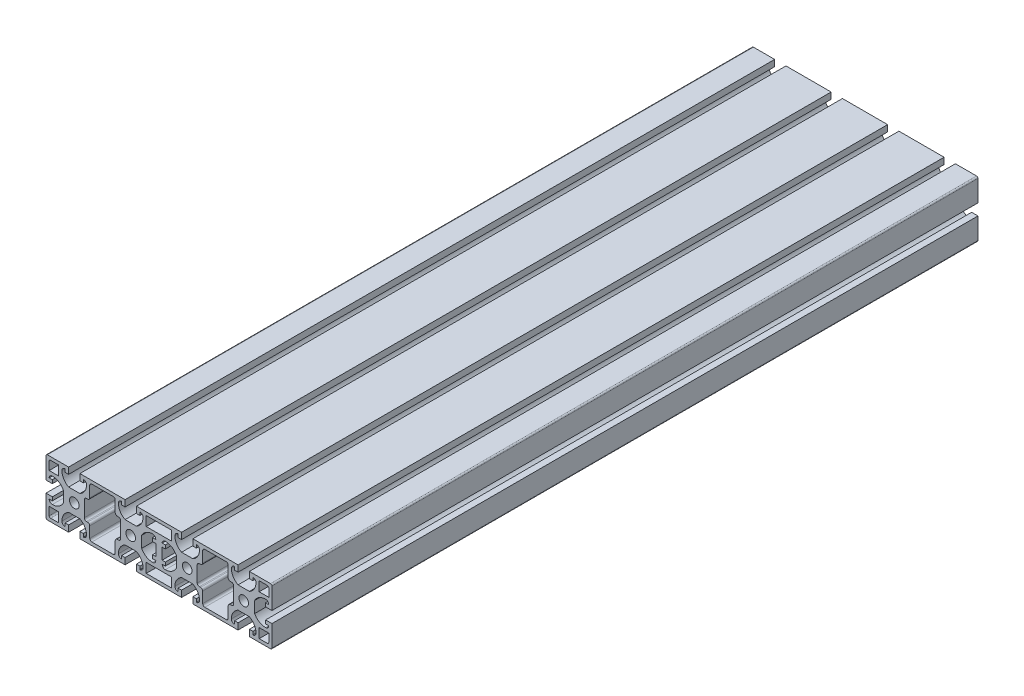
SolidWorks part; units mm, degrees
material "3.0255 (EN-AW 1350A)"
ref_plane "Płaszczyzna przednia" through (0, 0, 0) normal (0, 0, 1) x (1, 0, 0)
ref_plane "Płaszczyzna górna" through (0, 0, 0) normal (0, 1, 0) x (1, 0, 0)
ref_plane "Płaszczyzna prawa" through (0, 0, 0) normal (1, 0, 0) x (0, 0, -1)
sketch "Szkic1" plane through (0, 0, 0) normal (0, 0, 1) x (1, 0, 0)
  line L0 (0, 20) -> (0, -20) construction
  line L1 (-51.8865, 0) -> (40, 0) construction
  line L4 (-40, -20) -> (-40, 20)
  line L7 (-40, -20) -> (0, 0) construction
  line L8 (-40, 20) -> (40, -20) construction
  line L13 (20, 20) -> (20, 0) construction
  line L15 (24, 20) -> (24, 15.5)
  line L16 (24, 15.5) -> (26.4714, 15.5)
  line L21 (16, 15.5) -> (13.5286, 15.5)
  line L23 (16, 20) -> (13.5286, 20)
  line L24 (16, 20) -> (16, 15.5)
  line L25 (16, 7.75) -> (24, 7.75)
  line L26 (13.5286, 15.5) -> (13.5286, 17.75)
  line L27 (26.4714, 15.5) -> (26.4714, 17.75)
  line L28 (-24, 20) -> (-24, 15.5)
  line L29 (-26.4714, 15.5) -> (-26.4714, 17.75)
  line L30 (-24, 15.5) -> (-26.4714, 15.5)
  line L31 (-13.5286, 15.5) -> (-13.5286, 17.75)
  line L32 (-16, 15.5) -> (-13.5286, 15.5)
  line L33 (-16, 20) -> (-16, 15.5)
  line L34 (-16, 7.75) -> (-24, 7.75)
  line L35 (20, -20) -> (20, 0) construction
  line L36 (-40, -20) -> (0, 0) construction
  line L37 (-40, 20) -> (40, -20) construction
  line L38 (30.9714, -17.75) -> (36.75, -17.75)
  line L39 (-16, -7.75) -> (-24, -7.75)
  line L40 (-16, -20) -> (-16, -15.5)
  line L41 (-16, -15.5) -> (-13.5286, -15.5)
  line L42 (-13.5286, -15.5) -> (-13.5286, -17.75)
  line L43 (-24, -15.5) -> (-26.4714, -15.5)
  line L44 (-26.4714, -15.5) -> (-26.4714, -17.75)
  line L45 (-24, -20) -> (-24, -15.5)
  line L46 (26.4714, -15.5) -> (26.4714, -17.75)
  line L47 (13.5286, -15.5) -> (13.5286, -17.75)
  line L48 (16, -7.75) -> (24, -7.75)
  line L49 (16, -20) -> (16, -15.5)
  line L50 (16, -15.5) -> (13.5286, -15.5)
  line L51 (24, -15.5) -> (26.4714, -15.5)
  line L52 (24, -20) -> (24, -15.5)
  line L53 (40, -20) -> (0, 20) construction
  line L54 (35.5, 6.4714) -> (37.75, 6.4714)
  line L55 (35.5, 4) -> (35.5, 6.4714)
  line L56 (40, 4) -> (35.5, 4)
  line L57 (40, -4) -> (35.5, -4)
  line L58 (35.5, -4) -> (35.5, -6.4714)
  line L59 (35.5, -6.4714) -> (37.75, -6.4714)
  line L60 (27.75, 4) -> (27.75, -4)
  line L61 (-35.5, -6.4714) -> (-37.75, -6.4714)
  line L62 (-37.75, -4) -> (-35.5, -4)
  line L63 (-35.5, -4) -> (-35.5, -6.4714)
  line L64 (-35.5, 4) -> (-35.5, 6.4714)
  line L65 (-35.5, 6.4714) -> (-37.75, 6.4714)
  line L66 (-37.75, 4) -> (-35.5, 4)
  line L67 (-27.75, 4) -> (-27.75, -4)
  line L68 (-37.75, 4) -> (-37.75, -4)
  line L69 (40, -4) -> (40, -19)
  line L70 (40, 19) -> (40, 4)
  line L71 (-40, -20) -> (-24, -20)
  line L72 (-16, -20) -> (16, -20)
  line L73 (24, -20) -> (39, -20)
  line L74 (13.5286, 20) -> (-16, 20)
  line L75 (-24, 20) -> (-40, 20)
  line L76 (24, 20) -> (39, 20)
  line L77 (10.5286, 7.0902) -> (11.4095, 7.0902)
  line L78 (-7.5286, -17.75) -> (7.5286, -17.75)
  line L79 (-9.0286, -16.25) -> (-9.0286, -8.5902)
  line L80 (-7.5286, 17.75) -> (7.5286, 17.75)
  line L81 (9.0286, -16.25) -> (9.0286, -8.5902)
  line L82 (-9.0286, -17.75) -> (9.0286, 17.75) construction
  line L83 (-9.0286, 17.75) -> (9.0286, -17.75) construction
  line L84 (-11.4095, -7.0902) -> (-10.5286, -7.0902)
  line L85 (-12.9095, -5.5902) -> (-12.9095, 5.5902)
  line L86 (-11.4095, 7.0902) -> (-10.5286, 7.0902)
  line L87 (12.9095, -5.5902) -> (12.9095, 5.5902)
  line L88 (-12.9095, -7.0902) -> (0, 0) construction
  line L89 (-12.9095, 7.0902) -> (12.9095, -7.0902) construction
  line L90 (-9.0286, 8.5902) -> (-9.0286, 16.25)
  line L91 (-9.0286, 4.5143) -> (-9.0286, 4.9587)
  line L92 (-9.0286, -4.9587) -> (-9.0286, -4.5143)
  line L93 (9.0286, 8.5902) -> (9.0286, 16.25)
  line L94 (10.5286, -7.0902) -> (11.4095, -7.0902)
  line L96 (0, 0) -> (12.9095, 7.0902) construction
  line L98 (37.75, -10.9714) -> (37.75, -16.75)
  line L99 (30.9714, 10.9714) -> (37.75, 10.9714)
  line L100 (30.9714, 10.9714) -> (30.9714, 17.75)
  line L101 (30.9714, 17.75) -> (36.75, 17.75)
  line L102 (37.75, 10.9714) -> (37.75, 16.75)
  line L103 (30.9714, 10.9714) -> (37.75, 17.75) construction
  line L104 (30.9714, 17.75) -> (37.75, 10.9714) construction
  line L105 (30.9714, -10.9714) -> (37.75, -10.9714)
  line L106 (30.9714, -10.9714) -> (30.9714, -17.75)
  line L107 (-30.9714, -10.9714) -> (-30.9714, -17.75)
  line L108 (-30.9714, -10.9714) -> (-37.75, -10.9714)
  line L109 (-37.75, -10.9714) -> (-37.75, -16.75)
  line L110 (-30.9714, -17.75) -> (-36.75, -17.75)
  line L111 (-30.9714, 17.75) -> (-36.75, 17.75)
  line L112 (-37.75, 10.9714) -> (-37.75, 16.75)
  line L113 (-30.9714, 10.9714) -> (-37.75, 10.9714)
  line L114 (-30.9714, 10.9714) -> (-30.9714, 17.75)
  line L115 (-40, 52.1634) -> (-40, -64.8993) construction
  line L116 (-110.9714, 17.75) -> (-117.75, 10.9714) construction
  line L117 (-110.9714, 10.9714) -> (-117.75, 17.75) construction
  line L118 (-80, 0) -> (-92.9095, 7.0902) construction
  line L119 (-67.0905, 7.0902) -> (-92.9095, -7.0902) construction
  line L120 (-67.0905, -7.0902) -> (-80, 0) construction
  line L121 (-70.9714, 17.75) -> (-89.0286, -17.75) construction
  line L122 (-70.9714, -17.75) -> (-89.0286, 17.75) construction
  line L123 (-120, -20) -> (-80, 20) construction
  line L124 (-40, 20) -> (-120, -20) construction
  line L125 (-40, -20) -> (-80, 0) construction
  line L126 (-100, -20) -> (-100, 0) construction
  line L127 (-100, 20) -> (-100, 0) construction
  line L128 (-40, 20) -> (-120, -20) construction
  line L129 (-40, -20) -> (-80, 0) construction
  line L130 (-28.1135, 0) -> (-120, 0) construction
  line L131 (-80, 20) -> (-80, -20) construction
  line L132 (-49.0286, 10.9714) -> (-49.0286, 17.75)
  line L133 (-49.0286, 10.9714) -> (-42.25, 10.9714)
  line L134 (-42.25, 10.9714) -> (-42.25, 16.75)
  line L135 (-49.0286, 17.75) -> (-43.25, 17.75)
  line L136 (-49.0286, -17.75) -> (-43.25, -17.75)
  line L137 (-42.25, -10.9714) -> (-42.25, -16.75)
  line L138 (-49.0286, -10.9714) -> (-42.25, -10.9714)
  line L139 (-49.0286, -10.9714) -> (-49.0286, -17.75)
  line L140 (-110.9714, -10.9714) -> (-110.9714, -17.75)
  line L141 (-110.9714, -10.9714) -> (-117.75, -10.9714)
  line L142 (-117.75, 10.9714) -> (-117.75, 16.75)
  line L143 (-110.9714, 17.75) -> (-116.75, 17.75)
  line L144 (-110.9714, 10.9714) -> (-110.9714, 17.75)
  line L145 (-110.9714, 10.9714) -> (-117.75, 10.9714)
  line L146 (-117.75, -10.9714) -> (-117.75, -16.75)
  line L147 (-90.5286, -7.0902) -> (-91.4095, -7.0902)
  line L148 (-89.0286, 8.5902) -> (-89.0286, 16.25)
  line L149 (-70.9714, -4.9587) -> (-70.9714, -4.5143)
  line L150 (-70.9714, 4.5143) -> (-70.9714, 4.9587)
  line L151 (-70.9714, 8.5902) -> (-70.9714, 16.25)
  line L152 (-92.9095, -5.5902) -> (-92.9095, 5.5902)
  line L153 (-68.5905, 7.0902) -> (-69.4714, 7.0902)
  line L154 (-67.0905, -5.5902) -> (-67.0905, 5.5902)
  line L155 (-68.5905, -7.0902) -> (-69.4714, -7.0902)
  line L156 (-89.0286, -16.25) -> (-89.0286, -8.5902)
  line L157 (-72.4714, 17.75) -> (-87.5286, 17.75)
  line L158 (-70.9714, -16.25) -> (-70.9714, -8.5902)
  line L159 (-72.4714, -17.75) -> (-87.5286, -17.75)
  line L160 (-90.5286, 7.0902) -> (-91.4095, 7.0902)
  line L161 (-104, 20) -> (-119, 20)
  line L162 (-56, 20) -> (-40, 20)
  line L163 (-93.5286, 20) -> (-64, 20)
  line L164 (-104, -20) -> (-119, -20)
  line L165 (-64, -20) -> (-96, -20)
  line L166 (-40, -20) -> (-56, -20)
  line L167 (-120, 19) -> (-120, 4)
  line L168 (-120, -4) -> (-120, -19)
  line L169 (-42.25, 4) -> (-42.25, -4)
  line L170 (-52.25, 4) -> (-52.25, -4)
  line L171 (-42.25, 4) -> (-44.5, 4)
  line L172 (-44.5, 6.4714) -> (-42.25, 6.4714)
  line L173 (-44.5, 4) -> (-44.5, 6.4714)
  line L174 (-44.5, -4) -> (-44.5, -6.4714)
  line L175 (-42.25, -4) -> (-44.5, -4)
  line L176 (-44.5, -6.4714) -> (-42.25, -6.4714)
  line L177 (-107.75, 4) -> (-107.75, -4)
  line L178 (-115.5, -6.4714) -> (-117.75, -6.4714)
  line L179 (-115.5, -4) -> (-115.5, -6.4714)
  line L180 (-120, -4) -> (-115.5, -4)
  line L181 (-120, 4) -> (-115.5, 4)
  line L182 (-115.5, 4) -> (-115.5, 6.4714)
  line L183 (-115.5, 6.4714) -> (-117.75, 6.4714)
  line L184 (-104, -20) -> (-104, -15.5)
  line L185 (-104, -15.5) -> (-106.4714, -15.5)
  line L186 (-96, -15.5) -> (-93.5286, -15.5)
  line L187 (-96, -20) -> (-96, -15.5)
  line L188 (-96, -7.75) -> (-104, -7.75)
  line L189 (-93.5286, -15.5) -> (-93.5286, -17.75)
  line L190 (-106.4714, -15.5) -> (-106.4714, -17.75)
  line L191 (-56, -20) -> (-56, -15.5)
  line L192 (-53.5286, -15.5) -> (-53.5286, -17.75)
  line L193 (-56, -15.5) -> (-53.5286, -15.5)
  line L194 (-66.4714, -15.5) -> (-66.4714, -17.75)
  line L195 (-64, -15.5) -> (-66.4714, -15.5)
  line L196 (-64, -20) -> (-64, -15.5)
  line L197 (-64, -7.75) -> (-56, -7.75)
  line L198 (-110.9714, -17.75) -> (-116.75, -17.75)
  line L199 (-64, 7.75) -> (-56, 7.75)
  line L200 (-64, 20) -> (-64, 15.5)
  line L201 (-64, 15.5) -> (-66.4714, 15.5)
  line L202 (-66.4714, 15.5) -> (-66.4714, 17.75)
  line L203 (-56, 15.5) -> (-53.5286, 15.5)
  line L204 (-53.5286, 15.5) -> (-53.5286, 17.75)
  line L205 (-56, 20) -> (-56, 15.5)
  line L206 (-106.4714, 15.5) -> (-106.4714, 17.75)
  line L207 (-93.5286, 15.5) -> (-93.5286, 17.75)
  line L208 (-96, 7.75) -> (-104, 7.75)
  line L209 (-96, 20) -> (-96, 15.5)
  line L210 (-96, 20) -> (-93.5286, 20)
  line L211 (-96, 15.5) -> (-93.5286, 15.5)
  line L212 (-104, 15.5) -> (-106.4714, 15.5)
  line L213 (-104, 20) -> (-104, 15.5)
  line L215 (-43.25, 17.75) -> (-36.75, 17.75)
  line L216 (-42.25, 10.9714) -> (-37.75, 10.9714)
  line L217 (-42.25, -10.9714) -> (-37.75, -10.9714)
  line L218 (-43.25, -17.75) -> (-36.75, -17.75)
  circle A0 centre (-20, 0) radius 3.4
  circle A1 centre (20, 0) radius 3.4
  arc A2 (26.4714, 17.75) -> (28.7214, 15.5) centre (26.4714, 15.5) cw
  arc A3 (28.7214, 15.5) -> (24, 7.75) centre (20, 15.5) cw
  arc A4 (13.5286, 17.75) -> (11.2786, 15.5) centre (13.5286, 15.5) ccw
  arc A5 (11.2786, 15.5) -> (16, 7.75) centre (20, 15.5) ccw
  arc A6 (-26.4714, 17.75) -> (-28.7214, 15.5) centre (-26.4714, 15.5) ccw
  arc A7 (-13.5286, 17.75) -> (-11.2786, 15.5) centre (-13.5286, 15.5) cw
  arc A8 (-11.2786, 15.5) -> (-16, 7.75) centre (-20, 15.5) cw
  arc A9 (-28.7214, 15.5) -> (-24, 7.75) centre (-20, 15.5) ccw
  arc A10 (-28.7214, -15.5) -> (-24, -7.75) centre (-20, -15.5) cw
  arc A11 (-11.2786, -15.5) -> (-16, -7.75) centre (-20, -15.5) ccw
  arc A12 (-13.5286, -17.75) -> (-11.2786, -15.5) centre (-13.5286, -15.5) ccw
  arc A13 (-26.4714, -17.75) -> (-28.7214, -15.5) centre (-26.4714, -15.5) cw
  arc A14 (11.2786, -15.5) -> (16, -7.75) centre (20, -15.5) cw
  arc A15 (13.5286, -17.75) -> (11.2786, -15.5) centre (13.5286, -15.5) cw
  arc A16 (28.7214, -15.5) -> (24, -7.75) centre (20, -15.5) ccw
  arc A17 (26.4714, -17.75) -> (28.7214, -15.5) centre (26.4714, -15.5) ccw
  arc A18 (35.5, 8.7214) -> (27.75, 4) centre (35.5, 0) ccw
  arc A19 (37.75, 6.4714) -> (35.5, 8.7214) centre (35.5, 6.4714) ccw
  arc A20 (37.75, -6.4714) -> (35.5, -8.7214) centre (35.5, -6.4714) cw
  arc A21 (35.5, -8.7214) -> (27.75, -4) centre (35.5, 0) cw
  arc A22 (-35.5, -8.7214) -> (-27.75, -4) centre (-35.5, 0) ccw
  arc A23 (-37.75, -6.4714) -> (-35.5, -8.7214) centre (-35.5, -6.4714) ccw
  arc A24 (-37.75, 6.4714) -> (-35.5, 8.7214) centre (-35.5, 6.4714) cw
  arc A25 (-35.5, 8.7214) -> (-27.75, 4) centre (-35.5, 0) cw
  arc A26 (-10.5286, 7.0902) -> (-9.0286, 8.5902) centre (-10.5286, 8.5902) ccw
  arc A27 (-9.0286, -8.5902) -> (-10.5286, -7.0902) centre (-10.5286, -8.5902) ccw
  arc A28 (11.4095, -7.0902) -> (12.9095, -5.5902) centre (11.4095, -5.5902) ccw
  arc A29 (9.0286, -8.5902) -> (10.5286, -7.0902) centre (10.5286, -8.5902) cw
  arc A30 (7.5286, -17.75) -> (9.0286, -16.25) centre (7.5286, -16.25) ccw
  arc A31 (-7.5286, -17.75) -> (-9.0286, -16.25) centre (-7.5286, -16.25) cw
  arc A32 (-11.4095, -7.0902) -> (-12.9095, -5.5902) centre (-11.4095, -5.5902) cw
  arc A33 (-12.9095, 5.5902) -> (-11.4095, 7.0902) centre (-11.4095, 5.5902) cw
  arc A34 (-9.0286, 16.25) -> (-7.5286, 17.75) centre (-7.5286, 16.25) cw
  arc A35 (7.5286, 17.75) -> (9.0286, 16.25) centre (7.5286, 16.25) cw
  arc A36 (11.4095, 7.0902) -> (12.9095, 5.5902) centre (11.4095, 5.5902) cw
  arc A37 (10.5286, 7.0902) -> (9.0286, 8.5902) centre (10.5286, 8.5902) cw
  arc A40 (39, -20) -> (40, -19) centre (39, -19) ccw
  arc A41 (39, 20) -> (40, 19) centre (39, 19) cw
  arc A42 (36.75, 17.75) -> (37.75, 16.75) centre (36.75, 16.75) cw
  arc A43 (36.75, -17.75) -> (37.75, -16.75) centre (36.75, -16.75) ccw
  arc A44 (-36.75, -17.75) -> (-37.75, -16.75) centre (-36.75, -16.75) cw
  arc A45 (-36.75, 17.75) -> (-37.75, 16.75) centre (-36.75, 16.75) ccw
  arc A46 (-43.25, 17.75) -> (-42.25, 16.75) centre (-43.25, 16.75) cw
  arc A47 (-43.25, -17.75) -> (-42.25, -16.75) centre (-43.25, -16.75) ccw
  arc A48 (-116.75, -17.75) -> (-117.75, -16.75) centre (-116.75, -16.75) cw
  arc A49 (-116.75, 17.75) -> (-117.75, 16.75) centre (-116.75, 16.75) ccw
  arc A50 (-119, 20) -> (-120, 19) centre (-119, 19) ccw
  arc A51 (-119, -20) -> (-120, -19) centre (-119, -19) cw
  arc A54 (-90.5286, 7.0902) -> (-89.0286, 8.5902) centre (-90.5286, 8.5902) ccw
  arc A55 (-91.4095, 7.0902) -> (-92.9095, 5.5902) centre (-91.4095, 5.5902) ccw
  arc A56 (-87.5286, 17.75) -> (-89.0286, 16.25) centre (-87.5286, 16.25) ccw
  arc A57 (-70.9714, 16.25) -> (-72.4714, 17.75) centre (-72.4714, 16.25) ccw
  arc A58 (-67.0905, 5.5902) -> (-68.5905, 7.0902) centre (-68.5905, 5.5902) ccw
  arc A59 (-68.5905, -7.0902) -> (-67.0905, -5.5902) centre (-68.5905, -5.5902) ccw
  arc A60 (-72.4714, -17.75) -> (-70.9714, -16.25) centre (-72.4714, -16.25) ccw
  arc A61 (-87.5286, -17.75) -> (-89.0286, -16.25) centre (-87.5286, -16.25) cw
  arc A62 (-89.0286, -8.5902) -> (-90.5286, -7.0902) centre (-90.5286, -8.5902) ccw
  arc A63 (-91.4095, -7.0902) -> (-92.9095, -5.5902) centre (-91.4095, -5.5902) cw
  arc A64 (-70.9714, -8.5902) -> (-69.4714, -7.0902) centre (-69.4714, -8.5902) cw
  arc A65 (-69.4714, 7.0902) -> (-70.9714, 8.5902) centre (-69.4714, 8.5902) cw
  arc A66 (-44.5, 8.7214) -> (-52.25, 4) centre (-44.5, 0) ccw
  arc A67 (-42.25, 6.4714) -> (-44.5, 8.7214) centre (-44.5, 6.4714) ccw
  arc A68 (-42.25, -6.4714) -> (-44.5, -8.7214) centre (-44.5, -6.4714) cw
  arc A69 (-44.5, -8.7214) -> (-52.25, -4) centre (-44.5, 0) cw
  arc A70 (-115.5, -8.7214) -> (-107.75, -4) centre (-115.5, 0) ccw
  arc A71 (-117.75, -6.4714) -> (-115.5, -8.7214) centre (-115.5, -6.4714) ccw
  arc A72 (-117.75, 6.4714) -> (-115.5, 8.7214) centre (-115.5, 6.4714) cw
  arc A73 (-115.5, 8.7214) -> (-107.75, 4) centre (-115.5, 0) cw
  arc A74 (-106.4714, -17.75) -> (-108.7214, -15.5) centre (-106.4714, -15.5) cw
  arc A75 (-108.7214, -15.5) -> (-104, -7.75) centre (-100, -15.5) cw
  arc A76 (-93.5286, -17.75) -> (-91.2786, -15.5) centre (-93.5286, -15.5) ccw
  arc A77 (-91.2786, -15.5) -> (-96, -7.75) centre (-100, -15.5) ccw
  arc A78 (-53.5286, -17.75) -> (-51.2786, -15.5) centre (-53.5286, -15.5) ccw
  arc A79 (-66.4714, -17.75) -> (-68.7214, -15.5) centre (-66.4714, -15.5) cw
  arc A80 (-68.7214, -15.5) -> (-64, -7.75) centre (-60, -15.5) cw
  arc A81 (-51.2786, -15.5) -> (-56, -7.75) centre (-60, -15.5) ccw
  arc A82 (-51.2786, 15.5) -> (-56, 7.75) centre (-60, 15.5) cw
  arc A83 (-68.7214, 15.5) -> (-64, 7.75) centre (-60, 15.5) ccw
  arc A84 (-66.4714, 17.75) -> (-68.7214, 15.5) centre (-66.4714, 15.5) ccw
  arc A85 (-53.5286, 17.75) -> (-51.2786, 15.5) centre (-53.5286, 15.5) cw
  arc A86 (-91.2786, 15.5) -> (-96, 7.75) centre (-100, 15.5) cw
  arc A87 (-93.5286, 17.75) -> (-91.2786, 15.5) centre (-93.5286, 15.5) cw
  arc A88 (-108.7214, 15.5) -> (-104, 7.75) centre (-100, 15.5) ccw
  arc A89 (-106.4714, 17.75) -> (-108.7214, 15.5) centre (-106.4714, 15.5) ccw
  circle A90 centre (-100, 0) radius 3.4
  circle A91 centre (-60, 0) radius 3.4
  point P0 (-40, -19.1277)
  point P5 (0, 0)
  point P13 (-40, 19.1356)
  point P16 (-39.2749, 20)
  point P17 (0, 0)
  point P30 (24, 17.75)
  point P108 (0, 0)
  point P124 (-9.0286, 7.0902)
  point P132 (9.0286, -7.0902)
  point P156 (9.0286, 7.0902)
  point P161 (40, 20)
  point P162 (34.3607, 14.3607)
  point P364 (-114.3607, 14.3607)
  point P365 (-120, 20)
  point P366 (-89.0286, 7.0902)
  point P367 (-89.0286, -7.0902)
  point P368 (-70.9714, 7.0902)
  point P369 (-80, 0)
  point P370 (-80, 0)
  point P371 (-80, 0)
  dimension "D4" = 6.8
  dimension "D5" = 12.25
  dimension "D9" = 11
  dimension "D11" = 1.5
  dimension "D16" = 1
  dimension "D1" = 80
  dimension "D2" = 40
  dimension "D3" = 40
  dimension "D6" = 2.25
  dimension "D7" = 8
  dimension "D8" = 4.5
  dimension "D10" = 14.1804
  dimension "D13" = 2.25
  dimension "D14" = 2.25
  dimension "D15" = 2.25
extrude "Dodanie-wyciągnięcie1" add sketch "Szkic1" along normal blind 500
